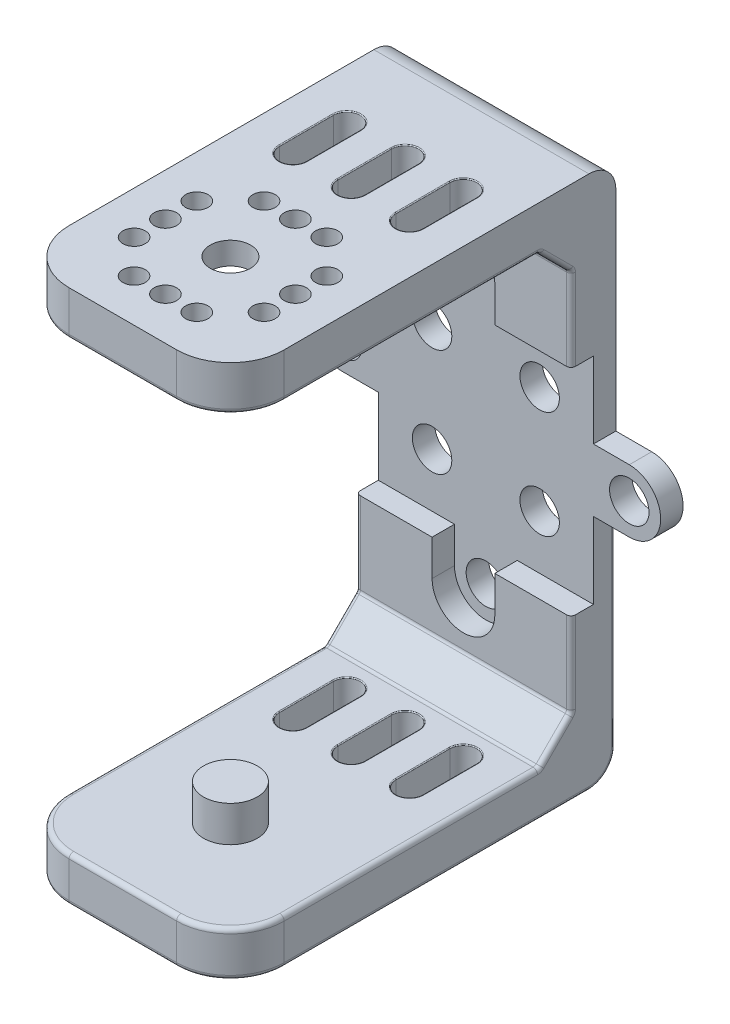
SolidWorks part; units mm, degrees
ref_plane "Front Plane" through (0, 0, 0) normal (0, 0, 1) x (1, 0, 0)
ref_plane "Top Plane" through (0, 0, 0) normal (0, 1, 0) x (1, 0, 0)
ref_plane "Right Plane" through (0, 0, 0) normal (1, 0, 0) x (0, 0, -1)
sketch "Sketch1" plane through (0, 0, 0) normal (1, 0, 0) x (0, 0, -1)
  line L0 (0, 59.7) -> (0, 0)
  line L1 (0, 0) -> (-43, 0)
  line L2 (-43, 0) -> (-43, 5)
  line L3 (-43, 5) -> (-8.5355, 5)
  line L4 (-5, 8.5355) -> (-5, 51.1645)
  line L5 (-8.5355, 54.7) -> (-43, 54.7)
  line L6 (-43, 54.7) -> (-43, 59.7)
  line L7 (-43, 59.7) -> (0, 59.7)
  line L8 (-8.5355, 54.7) -> (-5, 51.1645)
  line L9 (-5, 29.85) -> (0, 29.85) construction
  line L10 (-8.5355, 5) -> (-5, 8.5355)
  dimension "D1" = 49.7
  dimension "D2" = 5
  dimension "D3" = 5
  dimension "D4" = 5
  dimension "50" = 43
  dimension "D5" = 45
extrude "Boss-Extrude1" add sketch "Sketch1" along normal blind 24
sketch "Sketch2" plane through (0, 54.7, 0) normal (0, -1, 0) x (1, 0, 0)
  line L0 (24, 43) -> (0, 43) construction
  line L1 (12, 43) -> (12, 0) construction
  line L2 (24, 0) -> (0, 0) construction
  circle A0 centre (12, 31) radius 10.5
  dimension "D1" = 21
  dimension "D2" = 12
  dimension "D3" = 0
extrude "Cut-Extrude1" cut sketch "Sketch2" against normal blind 2.5
sketch "Sketch4" plane through (0, 57.2, 0) normal (0, -1, 0) x (1, 0, 0)
  circle A0 centre (12, 31) radius 2.25
  circle A1 centre (12, 31) radius 10.5 construction
  circle A2 centre (12, 38.25) radius 1.25
  circle A3 centre (8.5, 38.25) radius 1.25
  circle A4 centre (15.5, 38.25) radius 1.25
  circle A5 centre (19.25, 34.5) radius 1.25
  circle A6 centre (19.25, 31) radius 1.25
  circle A7 centre (19.25, 27.5) radius 1.25
  circle A8 centre (15.5, 23.75) radius 1.25
  circle A9 centre (12, 23.75) radius 1.25
  circle A10 centre (8.5, 23.75) radius 1.25
  circle A11 centre (4.75, 27.5) radius 1.25
  circle A12 centre (4.75, 31) radius 1.25
  circle A13 centre (4.75, 34.5) radius 1.25
  dimension "D1" = 4.5
  dimension "D2" = 0
  dimension "D3" = 2.5
  dimension "D4" = 7.25
  dimension "D5" = 3.5
  dimension "D6" = 3.5
  dimension "D7" = 4
extrude "Cut-Extrude2" cut sketch "Sketch4" against normal blind 10
fillet "Fillet2" radius 6 4 edges at (24, 2.5, 43) (0, 2.5, 43) (24, 57.2, 43) (0, 57.2, 43)
fillet "Fillet3" radius 3 2 edges at (12, 0, 0) (12, 59.7, 0)
sketch "Sketch9" plane through (0, 0, 5) normal (0, 0, 1) x (1, 0, 0)
  line L0 (0, 41.85) -> (8.5, 41.85)
  line L1 (0, 41.85) -> (0, 17.85)
  line L2 (0, 17.85) -> (8.5, 17.85)
  line L3 (24, 41.85) -> (24, 17.85)
  line L4 (0, 29.85) -> (24, 29.85) construction
  line L5 (24, 51.1645) -> (24, 8.5355) construction
  line L6 (0, 51.1645) -> (0, 8.5355) construction
  line L7 (8.5, 41.85) -> (8.5, 45.85)
  line L8 (15.5, 13.85) -> (15.5, 17.85)
  line L9 (15.5, 45.85) -> (15.5, 41.85)
  line L10 (8.5, 17.85) -> (8.5, 13.85)
  line L11 (15.5, 41.85) -> (24, 41.85)
  line L12 (15.5, 17.85) -> (24, 17.85)
  line L13 (24, 51.1645) -> (0, 51.1645) construction
  arc A0 (15.5, 45.85) -> (8.5, 45.85) centre (12, 45.85) ccw
  arc A1 (15.5, 13.85) -> (8.5, 13.85) centre (12, 13.85) cw
  dimension "D1" = 7
  dimension "D2" = 4
extrude "Cut-Extrude3" cut sketch "Sketch9" against normal blind 2.5
sketch "Sketch10" plane through (0, 0, 2.5) normal (0, 0, 1) x (1, 0, 0)
  line L0 (12, 41.85) -> (12, 17.85) construction
  line L3 (0, 29.85) -> (24, 29.85) construction
  line L4 (0, 41.85) -> (0, 17.85) construction
  line L5 (24, 17.85) -> (24, 41.85) construction
  line L9 (8.5, 45.85) -> (15.5, 45.85) construction
  circle A0 centre (6, 35.85) radius 2.2
  circle A1 centre (18, 35.85) radius 2.2
  circle A2 centre (18, 23.85) radius 2.2
  circle A3 centre (6, 23.85) radius 2.2
  circle A4 centre (12, 45.85) radius 2.2
  circle A5 centre (12, 13.85) radius 2.2
  point P8 (12, 29.85)
  point P23 (12, 29.85)
  dimension "D1" = 4.4
  dimension "D5" = 4.4
  dimension "D2" = 6
  dimension "D3" = 6
  dimension "D4" = 4
extrude "Cut-Extrude4" cut sketch "Sketch10" against normal blind 1000
sketch "Sketch11" plane through (0, 5, 0) normal (0, 1, 0) x (1, 0, 0)
  line L1 (18, -43) -> (6, -43) construction
  line L2 (12, -43) -> (12, -5) construction
  line L3 (24, -5) -> (0, -5) construction
  circle A0 centre (12, -31) radius 3
  dimension "D1" = 6
  dimension "D2" = 12
extrude "Boss-Extrude2" add sketch "Sketch11" along normal blind 4
sketch "Sketch12" plane through (0, 54.7, 0) normal (0, -1, 0) x (1, 0, 0)
  line L0 (12, 20.5) -> (24, 20.5) construction
  line L1 (24, 8.5355) -> (0, 8.5355) construction
  line L3 (12, 8.5355) -> (12, 20.5) construction
  line L7 (13.5, 11.5178) -> (13.5, 17.5178)
  line L9 (10.5, 11.5178) -> (10.5, 17.5178)
  line L13 (20, 11.5178) -> (20, 17.5178)
  line L14 (17, 11.5178) -> (17, 17.5178)
  line L15 (7, 11.5178) -> (7, 17.5178)
  line L16 (4, 11.5178) -> (4, 17.5178)
  line L18 (24, 20.5) -> (24, 8.5355) construction
  circle A0 centre (12, 31) radius 10.5 construction
  arc A1 (13.5, 17.5178) -> (10.5, 17.5178) centre (12, 17.5178) ccw
  arc A2 (13.5, 11.5178) -> (10.5, 11.5178) centre (12, 11.5178) cw
  arc A3 (20, 17.5178) -> (17, 17.5178) centre (18.5, 17.5178) ccw
  arc A4 (20, 11.5178) -> (17, 11.5178) centre (18.5, 11.5178) cw
  arc A5 (4, 11.5178) -> (7, 11.5178) centre (5.5, 11.5178) ccw
  arc A6 (4, 17.5178) -> (7, 17.5178) centre (5.5, 17.5178) cw
  point P22 (13.5, 14.5178)
  point P23 (10.5, 14.5178)
  point P40 (24, 14.5178)
  dimension "D1" = 3
  dimension "D3" = 6
  dimension "D5" = 6.5
  dimension "D4" = 2
extrude "Cut-Extrude5" cut sketch "Sketch12" against normal mid plane 130 contours A5 L15 A6 L16 | L7 A1 L9 A2 | L13 A3 L14 A4
sketch "Sketch14" plane through (0, 0, 0) normal (0, 0, -1) x (-1, 0, 0)
  line L0 (-24, 29.85) -> (0, 29.85) construction
  line L1 (-24, 3) -> (-24, 56.7) construction
  line L2 (0, 3) -> (0, 56.7) construction
  line L3 (-24, 33.35) -> (-28, 33.35)
  line L5 (-28, 26.35) -> (-24, 26.35)
  line L6 (-24, 26.35) -> (-24, 33.35)
  line L7 (-12, 56.7) -> (-12, 3) construction
  line L8 (0, 56.7) -> (-24, 56.7) construction
  line L9 (-24, 3) -> (0, 3) construction
  line L10 (0, 33.35) -> (4, 33.35)
  line L11 (0, 26.35) -> (0, 33.35)
  line L12 (4, 26.35) -> (0, 26.35)
  arc A0 (-28, 33.35) -> (-28, 26.35) centre (-28, 29.85) ccw
  arc A1 (4, 33.35) -> (4, 26.35) centre (4, 29.85) cw
  circle A2 centre (-28, 29.85) radius 2.2
  circle A3 centre (4, 29.85) radius 2.2
  point P12 (-24, 29.85)
  dimension "D3" = 4.4
  dimension "D1" = 4
  dimension "D2" = 7
extrude "Boss-Extrude3" add sketch "Sketch14" against normal up to surface (2.5 mm away) up to face at (8.2, 23.85, 2.5)
fillet "Fillet5" radius 0.1 48 edges at (20, 5, 14.5178) (18.5, 5, 10.0178) (17, 5, 14.5178) (13.5, 5, 14.5178) (12, 5, 10.0178) (10.5, 5, 14.5178) (4, 5, 14.5178) (5.5, 5, 10.0178) (7, 5, 14.5178) (18.5, 0, 19.0178) (20, 0, 14.5178) (18.5, 0, 10.0178) (5.5, 0, 19.0178) (4, 0, 14.5178) (5.5, 0, 10.0178) (12, 0, 19.0178) (13.5, 0, 14.5178) (12, 0, 10.0178) (17, 54.7, 14.5178) (18.5, 54.7, 19.0178) (20, 54.7, 14.5178) (12, 54.7, 19.0178) (13.5, 54.7, 14.5178) (12, 54.7, 10.0178) (5.5, 54.7, 19.0178) (7, 54.7, 14.5178) (5.5, 54.7, 10.0178) (12, 59.7, 10.0178) (13.5, 59.7, 14.5178) (12, 59.7, 19.0178) (5.5, 59.7, 10.0178) (7, 59.7, 14.5178) (5.5, 59.7, 19.0178) (18.5, 59.7, 10.0178) (20, 59.7, 14.5178) (18.5, 59.7, 19.0178) (18.5, 5, 19.0178) (12, 5, 19.0178) (5.5, 5, 19.0178) (17, 0, 14.5178) (7, 0, 14.5178) (10.5, 0, 14.5178) (18.5, 54.7, 10.0178) (10.5, 54.7, 14.5178) (4, 54.7, 14.5178) (10.5, 59.7, 14.5178) (4, 59.7, 14.5178) (17, 59.7, 14.5178)
fillet "Fillet6" radius 0.5 31 edges at (0, 46.5072, 5) (0, 13.1928, 5) (24, 46.5072, 5) (0, 52.9322, 6.7678) (0, 6.7678, 6.7678) (24, 52.9322, 6.7678) (24, 13.1928, 5) (24, 0.8787, 0.8787) (24, 0, 20) (22.2426, 0, 41.2426) (12, 0, 43) (1.7574, 0, 41.2426) (0, 0, 20) (0, 0.8787, 0.8787) (0, 14.675, 0) (0, 54.7, 22.7678) (1.7574, 54.7, 41.2426) (12, 54.7, 43) (22.2426, 54.7, 41.2426) (0, 5, 22.7678) (1.7574, 5, 41.2426) (12, 5, 43) (22.2426, 5, 41.2426) (12, 51.1645, 5) (24, 14.675, 0) (12, 54.7, 8.5355) (24, 54.7, 22.7678) (12, 8.5355, 5) (12, 5, 8.5355) (24, 6.7678, 6.7678) (24, 5, 22.7678)
